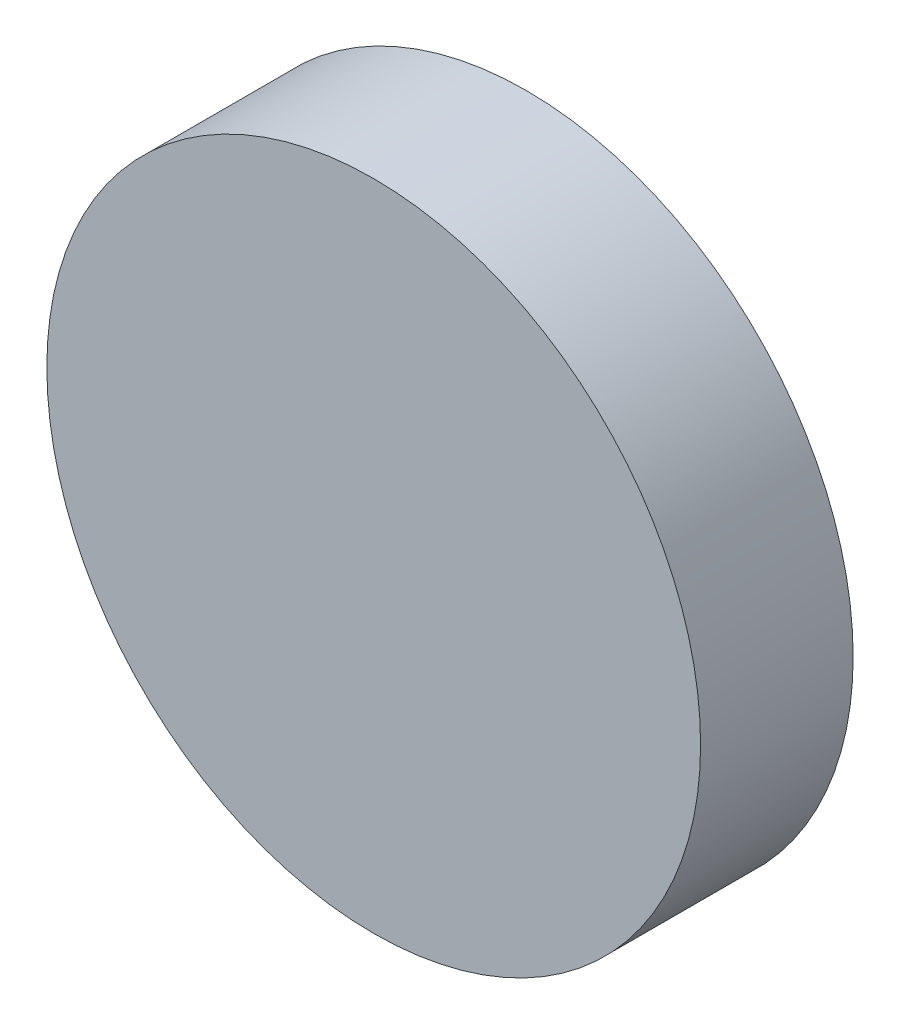
SolidWorks part; units mm, degrees
ref_plane "Front Plane" through (0, 0, 0) normal (0, 0, 1) x (1, 0, 0)
ref_plane "Top Plane" through (0, 0, 0) normal (0, 1, 0) x (1, 0, 0)
ref_plane "Right Plane" through (0, 0, 0) normal (1, 0, 0) x (0, 0, -1)
sketch "Sketch1" plane through (0, 0, 0) normal (0, 0, 1) x (1, 0, 0)
  circle A0 centre (0, 0) radius 10.8839
  dimension "D1" = 21.7678
extrude "Boss-Extrude1" add sketch "Sketch1" along normal blind 5.08 contours A0
sketch "Sketch2" plane through (0, 0, 0) normal (0, 0, -1) x (-1, 0, 0)
  circle A0 centre (0, 0) radius 3.937
  dimension "D1" = 7.874
extrude "Boss-Extrude2" add sketch "Sketch2" along normal blind 3.302
